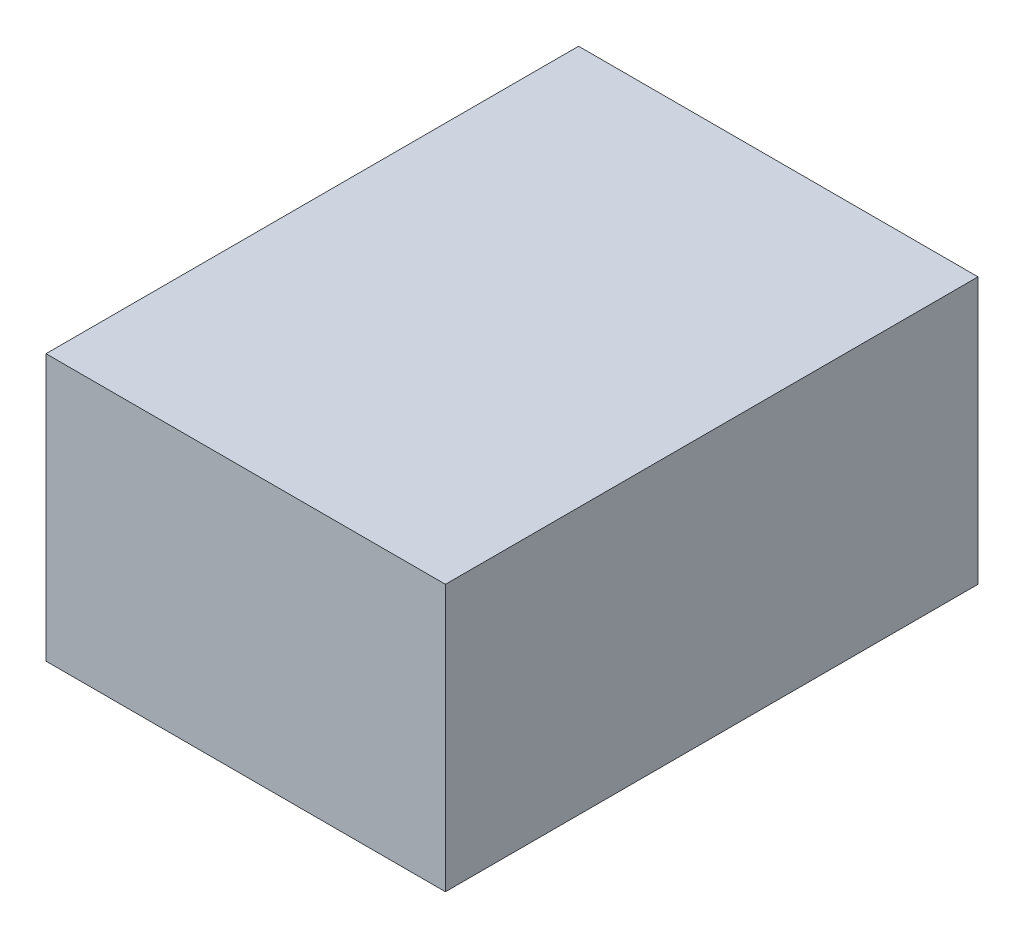
SolidWorks part; units mm, degrees
ref_plane "前视基准面" through (0, 0, 0) normal (0, 0, 1) x (1, 0, 0)
ref_plane "上视基准面" through (0, 0, 0) normal (0, 1, 0) x (1, 0, 0)
ref_plane "右视基准面" through (0, 0, 0) normal (1, 0, 0) x (0, 0, -1)
sketch "草图1" plane through (0, 0, 0) normal (0, 1, 0) x (1, 0, 0)
  line L1 (-19.3896, 16.9659) -> (-13.3896, 16.9659)
  line L2 (-19.3896, 16.9659) -> (-19.3896, 8.9659)
  line L3 (-19.3896, 8.9659) -> (-13.3896, 8.9659)
  line L4 (-13.3896, 16.9659) -> (-13.3896, 8.9659)
  dimension "D1" = 6
  dimension "D2" = 8
extrude "凸台-拉伸1" add sketch "草图1" along normal blind 4
